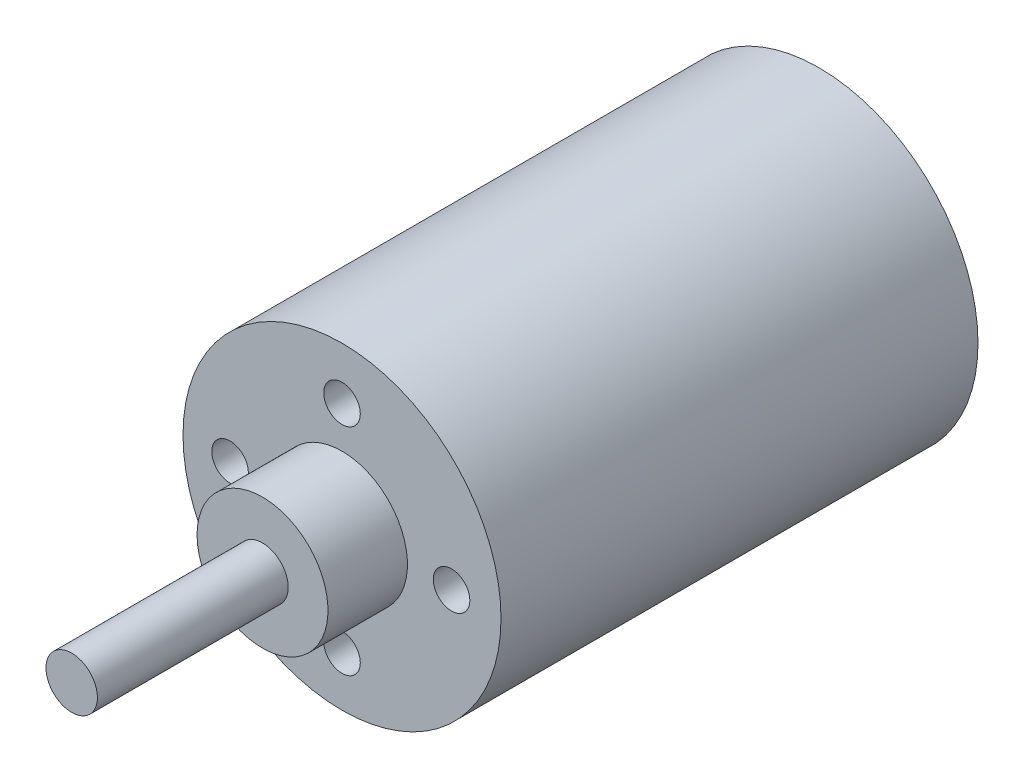
SolidWorks part; units mm, degrees
ref_plane "Plano frontal" through (0, 0, 0) normal (0, 0, 1) x (1, 0, 0)
ref_plane "Plano superior" through (0, 0, 0) normal (0, 1, 0) x (1, 0, 0)
ref_plane "Plano direito" through (0, 0, 0) normal (1, 0, 0) x (0, 0, -1)
sketch "Esboço1" plane through (0, 0, 0) normal (1, 0, 0) x (0, 0, -1)
  line L0 (-336.2789, 0) -> (16477.6681, 0) construction
  line L1 (0, -336.2789) -> (0, 16477.6681) construction
  line L2 (-15, 10) -> (15, 10)
  line L3 (15, 10) -> (15, 0)
  line L4 (15, 0) -> (-32, 0)
  line L5 (-15, 10) -> (-15, 4.1165)
  line L6 (336.2789, 0) -> (-16477.6681, 0) construction
  line L7 (-15, 4.1165) -> (-20, 4.1165)
  line L8 (-20, 4.1165) -> (-20, 1.6165)
  line L10 (-20, 1.6165) -> (-32, 1.6165)
  line L11 (-32, 1.6165) -> (-32, 0)
  point P8 (0, 10)
  point P13 (0, -10.0229)
  dimension "D1" = 15
  dimension "D2" = 2.5
  dimension "D3" = 5
  dimension "D4" = 12
  dimension "D5" = 10
revolve "Revolução1" add sketch "Esboço1" angle 360 about L4
hole_wizard "Broca de rosquear para helicoide M2.21" positions "Esboço3" profile "Esboço4" hole size "M2.2x0.45" standard "Ansi Metric"
sketch "Esboço3" plane through (0, 0, 15) normal (0, 0, 1) x (1, 0, 0)
  point P0 (0, 6.7192)
  point P2 (6.8894, 0)
  point P4 (0, -6.8389)
  point P6 (-7.0411, 0)
sketch "Esboço4" plane through (0, 6.7192, 15) normal (1, 0, 0) x (0, -1, 0)
  line L0 (0, 0) -> (0, 3.691)
  line L1 (0, 3.691) -> (1.15, 3)
  line L2 (1.15, 3) -> (1.15, 0)
  line L5 (1.15, 0) -> (0, 0)
  line L10 (0, 3.691) -> (-1.15, 3) construction
  line L11 (0, -6.35) -> (0, 107.95) construction
  dimension "Hole Dia." = 2.3
  dimension "Hole Depth" = 3
  dimension "Drill Angle" = 118
